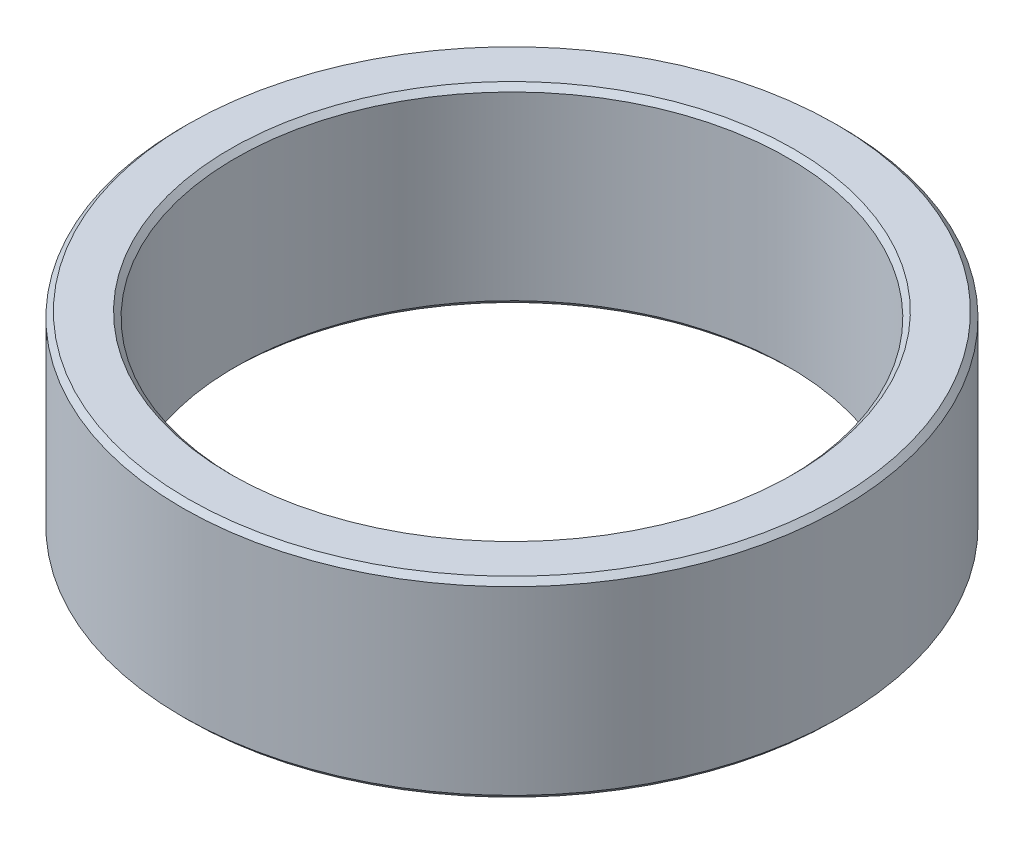
SolidWorks part; units mm, degrees
ref_plane "Piano frontale" through (0, 0, 0) normal (0, 0, 1) x (1, 0, 0)
ref_plane "Piano superiore" through (0, 0, 0) normal (0, 1, 0) x (1, 0, 0)
ref_plane "Piano destro" through (0, 0, 0) normal (1, 0, 0) x (0, 0, -1)
sketch "Schizzo1" plane through (0, 0, 0) normal (0, 1, 0) x (1, 0, 0)
  circle A0 centre (0, 0) radius 31
  circle A1 centre (0, 0) radius 26
  dimension "D1" = 62
  dimension "D2" = 52
extrude "Estrusione1" add sketch "Schizzo1" along normal blind 18
chamfer "Smusso1" distance 0.5 angle 45 4 edges at (0, 0, 26) (0, 0, 31) (0, 18, 26) (0, 18, 31)
